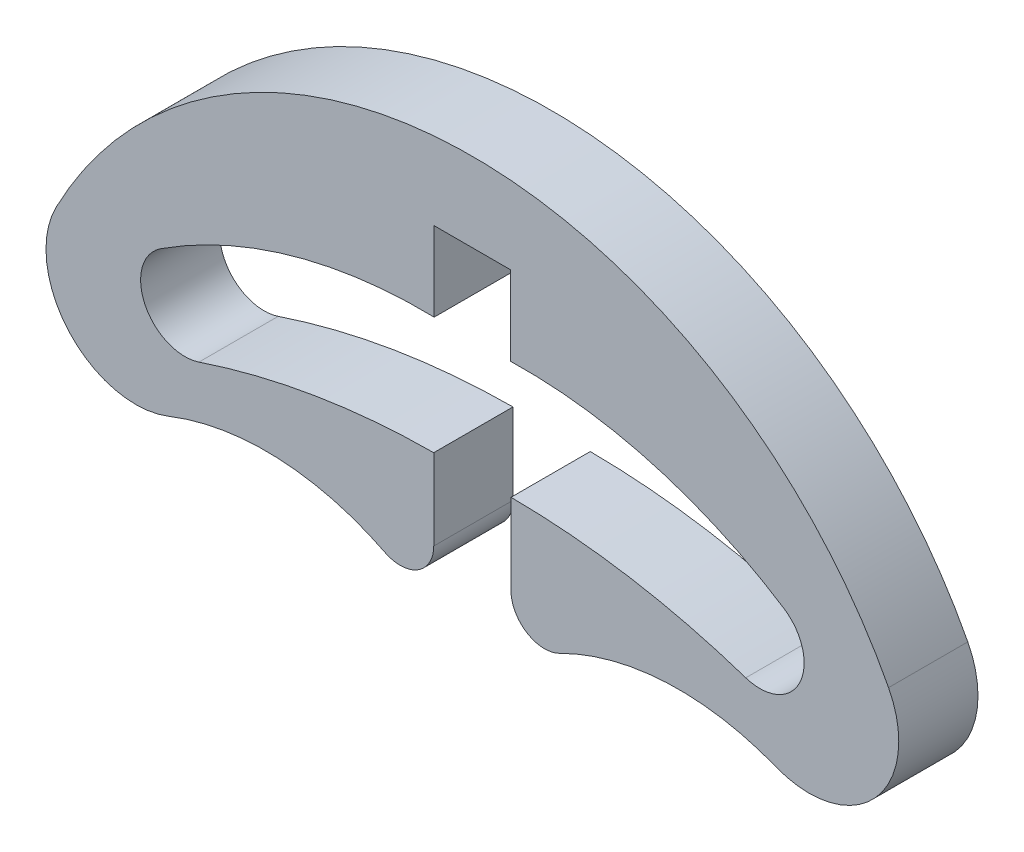
SolidWorks part; units mm, degrees
material "Acrylic (Medium-high impact)"
ref_plane "Front Plane" through (0, 0, 0) normal (0, 0, 1) x (1, 0, 0)
ref_plane "Top Plane" through (0, 0, 0) normal (0, 1, 0) x (1, 0, 0)
ref_plane "Right Plane" through (0, 0, 0) normal (1, 0, 0) x (0, 0, -1)
sketch "스케치1" plane through (0, 0, 0) normal (0, 0, 1) x (1, 0, 0)
  line L0 (0, 10.85) -> (0, 0) construction
  line L7 (0, 0) -> (0, -5.0766) construction
  line L8 (-1.4119, -8.0418) -> (1.1806, -8.0418) construction
  line L10 (-1.4119, -2.1114) -> (1.4119, -2.1114) construction
  line L12 (-1.4119, -8.0418) -> (1.4119, -2.1114) construction
  line L13 (-1.4119, -2.1114) -> (1.1806, -8.0418) construction
  line L15 (-1.875, 1.7135) -> (1.875, 1.7135) construction
  line L17 (0, -5.0305) -> (0, 0) construction
  line L18 (-1.4475, 2.128) -> (1.4475, 2.128) construction
  line L26 (-1.4475, 2.128) -> (-1.4475, 5.128)
  line L27 (-1.4475, 5.128) -> (1.4475, 5.128)
  line L28 (1.4475, 2.128) -> (1.4475, 5.128)
  line L29 (-1.4475, 2.128) -> (1.4475, 5.128) construction
  line L30 (-1.4475, 5.128) -> (1.4475, 2.128) construction
  line L31 (-1.5, -8.128) -> (1.5, -8.128) construction
  line L32 (-1.3116, -7.8451) -> (-1.3116, -2.3221)
  line L33 (-1.3116, -2.3221) -> (1.3116, -2.3221) construction
  line L34 (1.3116, -7.8451) -> (1.3116, -2.3221)
  line L35 (-1.5, -8.128) -> (1.3116, -2.3221) construction
  line L36 (-1.3116, -2.3221) -> (1.5, -8.128) construction
  circle A0 centre (0, 0) radius 8.128 construction
  circle A1 centre (0, 0) radius 2.54 construction
  arc A3 (0, 8.128) -> (15.7567, -1.4162) centre (0, -9.6506) cw
  arc A4 (15.7567, -1.4162) -> (11.4982, -6.1463) centre (12.7473, -2.9889) cw
  arc A5 (11.4982, -6.1463) -> (1.3116, -7.8451) centre (7.8156, -15.4546) ccw
  arc A6 (-11.4982, -6.1463) -> (-1.3116, -7.8451) centre (-7.8156, -15.4546) cw
  arc A7 (-15.7567, -1.4162) -> (-11.4982, -6.1463) centre (-12.7473, -2.9889) ccw
  arc A8 (0, 8.128) -> (-15.7567, -1.4162) centre (0, -9.6506) ccw
  arc A9 (-1.4475, 2.128) -> (-11.7969, -0.8011) centre (-1.8838, -16.0788) ccw
  arc A10 (-11.7969, -0.8011) -> (-10.3516, -3.7968) centre (-10.8844, -2.2074) ccw
  arc A11 (-10.3516, -3.7968) -> (-1.3116, -2.3221) centre (-1.3116, -30.7662) cw
  arc A12 (10.3516, -3.7968) -> (1.3116, -2.3221) centre (1.3116, -30.7662) ccw
  arc A13 (11.7969, -0.8011) -> (10.3516, -3.7968) centre (10.8844, -2.2074) cw
  arc A14 (1.4475, 2.128) -> (11.7969, -0.8011) centre (1.8838, -16.0788) cw
  ellipse E0 centre (0, 0) end of major axis (0, -8.128) minor radius 5.0153 (1.3116, -7.8451) -> (-1.3116, -7.8451) ccw construction
  ellipse E1 centre (0, 0) end of major axis (0, -3.0585) minor radius 2.0153 (-1.4475, 2.128) -> (-1.3116, -2.3221) ccw construction
  ellipse E2 centre (0, 0) end of major axis (0, -3.0585) minor radius 2.0153 (1.3116, -2.3221) -> (1.4475, 2.128) ccw construction
  point P2 (0, 10.85)
  point P5 (0, 2.8708)
  point P7 (0, 3.628)
  point P10 (-0.0603, -5.2033)
  point P30 (0, -5.0305)
  dimension "D1" = 5.588
  dimension "D2" = 5.08
  dimension "D6" = 2.895
  dimension "D3" = 3
  dimension "D4" = 3
  dimension "D5" = 2.5925
  dimension "D7" = 3
  dimension "D8" = 3
extrude "보스-돌출1" add sketch "스케치1" along normal blind 3
sketch "스케치2" plane through (0, 0, 3) normal (0, 0, 1) x (1, 0, 0)
  line L0 (0, -5.2332) -> (0, 0) construction
  line L1 (-1.4625, -9.2623) -> (1.4625, -9.2623)
  line L2 (-1.4625, -9.2623) -> (-1.4625, -1.2042)
  line L3 (-1.4625, -1.2042) -> (1.4625, -1.2042)
  line L4 (1.4625, -9.2623) -> (1.4625, -1.2042)
  line L5 (-1.4625, -9.2623) -> (1.4625, -1.2042) construction
  line L6 (-1.4625, -1.2042) -> (1.4625, -9.2623) construction
  point P0 (0, -5.2332)
  dimension "D1" = 2.925
extrude "컷-돌출1" cut sketch "스케치2" against normal up to surface (3 mm away) up to face at (0, -1.2316, 0)
fillet "필렛1" radius 1.27 2 edges at (1.4625, -7.7187, 1.5) (-1.4625, -7.7187, 1.5)
